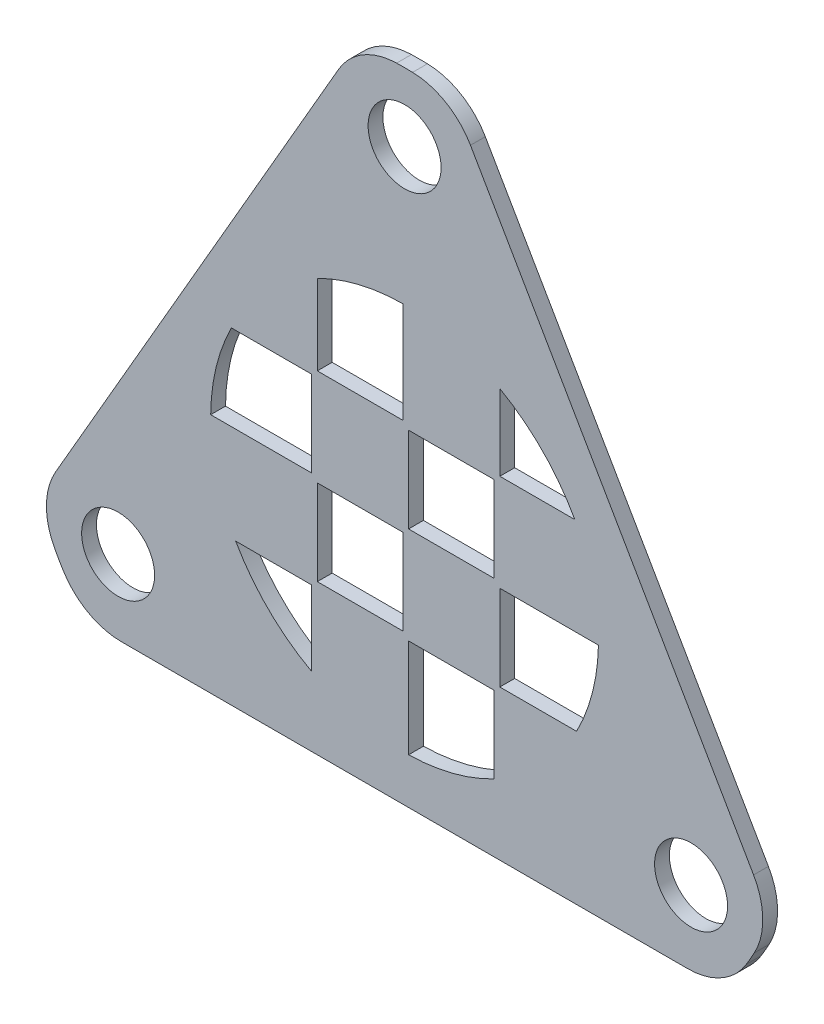
SolidWorks part; units mm, degrees
ref_plane "Спереди" through (0, 0, 0) normal (0, 0, 1) x (1, 0, 0)
ref_plane "Сверху" through (0, 0, 0) normal (0, 1, 0) x (1, 0, 0)
ref_plane "Справа" through (0, 0, 0) normal (1, 0, 0) x (0, 0, -1)
sketch "Sketch1" plane through (0, 0, 0) normal (0, 0, 1) x (1, 0, 0)
  line L0 (3.9, 6.755) -> (7.8, 0) construction
  line L2 (5.85, 10.1325) -> (11.7, 0) construction
  line L4 (7.8, 13.51) -> (15.6, 0) construction
  circle A61 centre (0, 0) radius 20
  circle A131 centre (0, 0) radius 1.25
  circle A484 centre (3.9, 0) radius 1.25
  circle A485 centre (7.8, 0) radius 1.25
  circle A486 centre (11.7, 0) radius 1.25
  circle A487 centre (15.6, 0) radius 1.25
  circle A488 centre (1.95, -3.3775) radius 1.25
  circle A489 centre (3.9, -6.755) radius 1.25
  circle A490 centre (5.85, -10.1325) radius 1.25
  circle A491 centre (7.8, -13.51) radius 1.25
  circle A492 centre (-1.95, -3.3775) radius 1.25
  circle A493 centre (-3.9, -6.755) radius 1.25
  circle A494 centre (-5.85, -10.1325) radius 1.25
  circle A495 centre (-7.8, -13.51) radius 1.25
  circle A496 centre (-3.9, 0) radius 1.25
  circle A497 centre (-7.8, 0) radius 1.25
  circle A498 centre (-11.7, 0) radius 1.25
  circle A499 centre (-15.6, 0) radius 1.25
  circle A500 centre (-1.95, 3.3775) radius 1.25
  circle A501 centre (-3.9, 6.755) radius 1.25
  circle A502 centre (-5.85, 10.1325) radius 1.25
  circle A503 centre (-7.8, 13.51) radius 1.25
  circle A504 centre (1.95, 3.3775) radius 1.25
  circle A505 centre (3.9, 6.755) radius 1.25
  circle A506 centre (5.85, 10.1325) radius 1.25
  circle A507 centre (7.8, 13.51) radius 1.25
  circle A508 centre (5.85, 3.3775) radius 1.25
  circle A509 centre (7.8, 6.755) radius 1.25
  circle A510 centre (9.75, 3.3775) radius 1.25
  circle A511 centre (11.7, 6.755) radius 1.25
  circle A512 centre (9.7491, 10.1341) radius 1.25
  circle A513 centre (13.6509, 3.3759) radius 1.25
  circle A514 centre (5.85, -3.3791) radius 1.25
  circle A515 centre (9.75, -3.3791) radius 1.25
  circle A516 centre (7.8, -6.7566) radius 1.25
  circle A517 centre (11.7, -6.7566) radius 1.25
  circle A518 centre (9.7491, -10.1356) radius 1.25
  circle A519 centre (13.6509, -3.3775) radius 1.25
  circle A520 centre (-0.0013, -6.7573) radius 1.25
  circle A521 centre (1.9487, -10.1348) radius 1.25
  circle A522 centre (-1.9513, -10.1348) radius 1.25
  circle A523 centre (-0.0013, -13.5123) radius 1.25
  circle A524 centre (-3.9032, -13.5123) radius 1.25
  circle A525 centre (3.9005, -13.5123) radius 1.25
  circle A526 centre (-5.8527, -3.3791) radius 1.25
  circle A527 centre (-7.8027, -6.7566) radius 1.25
  circle A528 centre (-9.7527, -3.3791) radius 1.25
  circle A529 centre (-11.7027, -6.7566) radius 1.25
  circle A530 centre (-13.6536, -3.3775) radius 1.25
  circle A531 centre (-9.7518, -10.1356) radius 1.25
  circle A532 centre (-5.8527, 3.3775) radius 1.25
  circle A533 centre (-9.7527, 3.3775) radius 1.25
  circle A534 centre (-7.8027, 6.755) radius 1.25
  circle A535 centre (-11.7027, 6.755) radius 1.25
  circle A536 centre (-9.7518, 10.1341) radius 1.25
  circle A537 centre (-13.6536, 3.3759) radius 1.25
  circle A538 centre (-0.0014, 6.7558) radius 1.25
  circle A539 centre (-1.9514, 10.1333) radius 1.25
  circle A540 centre (1.9486, 10.1333) radius 1.25
  circle A541 centre (-0.0014, 13.5108) radius 1.25
  circle A542 centre (3.9005, 13.5108) radius 1.25
  circle A543 centre (-3.9032, 13.5108) radius 1.25
  circle A544 centre (13.65, -1.1258) radius 2.2517 construction
  circle A545 centre (11.7009, -4.5044) radius 2.2522 construction
  circle A546 centre (9.75, -7.8834) radius 2.2522 construction
  circle A547 centre (7.7987, -11.2591) radius 2.2509 construction
  circle A548 centre (13.65, -1.1258) radius 0.65
  circle A549 centre (11.7009, -4.5044) radius 0.65
  circle A550 centre (9.75, -7.8834) radius 0.65
  circle A551 centre (7.7987, -11.2591) radius 0.65
  circle A552 centre (9.75, -1.1258) radius 0.65
  circle A553 centre (7.8009, -4.5044) radius 0.65
  circle A554 centre (5.85, -7.8834) radius 0.65
  circle A555 centre (3.8987, -11.2591) radius 0.65
  circle A556 centre (5.85, -1.1258) radius 0.65
  circle A557 centre (3.9009, -4.5044) radius 0.65
  circle A558 centre (1.95, -7.8834) radius 0.65
  circle A559 centre (-0.0013, -11.2591) radius 0.65
  circle A560 centre (1.95, -1.1258) radius 0.65
  circle A561 centre (0.0009, -4.5044) radius 0.65
  circle A562 centre (-1.95, -7.8834) radius 0.65
  circle A563 centre (-3.9013, -11.2591) radius 0.65
  circle A564 centre (-1.95, -1.1258) radius 0.65
  circle A565 centre (-3.8991, -4.5044) radius 0.65
  circle A566 centre (-5.85, -7.8834) radius 0.65
  circle A567 centre (-7.8013, -11.2591) radius 0.65
  circle A568 centre (-5.85, -1.1258) radius 0.65
  circle A569 centre (-7.7991, -4.5044) radius 0.65
  circle A570 centre (-9.75, -7.8834) radius 0.65
  circle A572 centre (-9.75, -1.1258) radius 0.65
  circle A573 centre (-11.6991, -4.5044) radius 0.65
  circle A576 centre (-13.65, -1.1258) radius 0.65
  circle A587 centre (0, 2.2517) radius 2.2517 construction
  circle A588 centre (0, 2.2517) radius 0.65
  circle A589 centre (3.9, 2.2517) radius 0.65
  circle A590 centre (7.8, 2.2517) radius 0.65
  circle A591 centre (11.7, 2.2517) radius 0.65
  circle A592 centre (15.6, 2.2517) radius 0.65
  circle A593 centre (1.9491, 5.6297) radius 2.2522 construction
  circle A594 centre (1.9491, 5.6297) radius 0.65
  circle A595 centre (5.8491, 5.6297) radius 0.65
  circle A596 centre (9.7491, 5.6297) radius 0.65
  circle A597 centre (13.6491, 5.6297) radius 0.65
  circle A598 centre (3.8991, 9.0072) radius 2.2522 construction
  circle A599 centre (3.8991, 9.0072) radius 0.65
  circle A600 centre (7.7991, 9.0072) radius 0.65
  circle A601 centre (11.6991, 9.0072) radius 0.65
  circle A602 centre (5.85, 12.3842) radius 2.2517 construction
  circle A603 centre (5.85, 12.3842) radius 0.65
  circle A604 centre (9.75, 12.3842) radius 0.65
  circle A605 centre (5.85, -14.6358) radius 0.65
  circle A606 centre (1.9509, -14.6353) radius 0.65
  circle A607 centre (-1.9491, -14.6353) radius 0.65
  circle A608 centre (-5.85, -14.6358) radius 0.65
  circle A609 centre (-15.6, 2.2517) radius 0.65
  circle A610 centre (-13.65, 5.6281) radius 0.65
  circle A611 centre (-11.7, 9.0056) radius 0.65
  circle A612 centre (-9.75, 12.3842) radius 0.65
  circle A613 centre (-5.85, 12.3842) radius 0.65
  circle A614 centre (-1.95, 12.3842) radius 0.65
  circle A615 centre (1.95, 12.3842) radius 0.65
  circle A616 centre (-7.8, 9.0056) radius 0.65
  circle A617 centre (-9.75, 5.6281) radius 0.65
  circle A618 centre (-11.7, 2.2517) radius 0.65
  circle A619 centre (-3.9, 9.0056) radius 0.65
  circle A620 centre (-5.85, 5.6281) radius 0.65
  circle A621 centre (-7.8, 2.2517) radius 0.65
  circle A622 centre (0, 9.0056) radius 0.65
  circle A623 centre (-1.95, 5.6281) radius 0.65
  circle A624 centre (-3.9, 2.2517) radius 0.65
  circle A625 centre (-15.5991, -4.5044) radius 0.65
  circle A626 centre (-13.65, -7.8834) radius 0.65
  circle A627 centre (-17.55, -7.8834) radius 0.65
  circle A628 centre (-19.5013, -11.2591) radius 0.65
  circle A629 centre (-15.6013, -11.2591) radius 0.65
  circle A630 centre (-11.7013, -11.2591) radius 0.65
  point P51 (0, 0)
  point P125 (-0.0013, -0.0008)
  point P231 (0, 0)
  dimension "D1" = 5
  dimension "D3" = 6
  dimension "D5" = 8
  dimension "D7" = 4
  dimension "D11" = 4
  dimension "D2" = 6
  dimension "D6" = 5
  dimension "D8" = 3
  dimension "D9" = 2
  dimension "D4" = 1.3
  dimension "D10" = 3
ref_plane "Plane1" through (0, 0, 10) normal (0, 0, 1) x (1, 0, 0)
sketch "Sketch2" plane through (0, 0, 10) normal (0, 0, 1) x (1, 0, 0)
  line L0 (-7.65, -15.1815) -> (-7.65, -8.35)
  line L2 (0.35, -16.9964) -> (0.35, -8.35)
  line L4 (-0.15, -16.9993) -> (-0.15, -8.35)
  line L5 (0.1469, -16.9994) -> (0.0704, -8.15) construction
  line L8 (-8.15, -14.919) -> (-8.15, -8.35)
  line L15 (16.9993, 0.15) -> (8.35, 0.15)
  line L17 (16.9964, -0.35) -> (8.35, -0.35)
  line L22 (14.919, 8.15) -> (8.35, 8.15)
  line L24 (15.1815, 7.65) -> (8.35, 7.65)
  line L26 (15.079, -7.85) -> (8.35, -7.85)
  line L28 (14.808, -8.35) -> (8.35, -8.35)
  line L33 (7.85, -15.079) -> (7.85, -8.35)
  line L34 (8.35, -14.808) -> (8.35, -8.35)
  line L36 (7.85, -7.85) -> (7.85, -0.35)
  line L37 (8.35, -7.85) -> (8.35, -0.35)
  line L38 (7.85, -8.35) -> (0.35, -8.35)
  line L39 (7.85, -7.85) -> (0.35, -7.85)
  line L40 (-0.15, -8.35) -> (-7.65, -8.35)
  line L41 (-0.15, -7.85) -> (-7.65, -7.85)
  line L42 (-0.15, -7.85) -> (-0.15, -0.35)
  line L43 (-0.0704, -8.15) -> (-0.1469, -16.9994) construction
  line L44 (0.0678, -7.85) -> (0, 0) construction
  line L45 (0.35, -7.85) -> (0.35, -0.35)
  line L46 (-8.15, -7.85) -> (-15.079, -7.85)
  line L47 (-8.15, -7.85) -> (-8.15, -0.35)
  line L48 (-7.65, -7.85) -> (-7.65, -0.35)
  line L49 (-8.15, -8.35) -> (-14.808, -8.35)
  line L50 (0.003, -0.35) -> (-0.0013, -0.35)
  line L53 (0.0013, 0.15) -> (-0.0013, 0.15)
  line L54 (-0.15, 0.15) -> (-7.65, 0.15)
  line L55 (-0.15, -0.35) -> (-7.65, -0.35)
  line L56 (7.85, -0.35) -> (0.35, -0.35)
  line L59 (7.85, 0.15) -> (0.35, 0.15)
  line L60 (7.85, 0.15) -> (7.85, 7.65)
  line L61 (8.35, 0.15) -> (8.35, 7.65)
  line L62 (-8.15, -0.35) -> (-16.9964, -0.35)
  line L65 (-8.15, 0.15) -> (-16.9993, 0.15)
  line L66 (-8.15, 0.15) -> (-8.15, 7.65)
  line L67 (-7.65, 0.15) -> (-7.65, 7.65)
  line L68 (-0.15, 0.15) -> (-0.15, 7.65)
  line L70 (0, 0) -> (-0.0678, -7.85) construction
  line L71 (0.35, 0.15) -> (0.35, 7.65)
  line L72 (7.85, 8.15) -> (7.85, 15.079)
  line L73 (8.35, 8.15) -> (8.35, 14.808)
  line L74 (7.85, 7.65) -> (0.35, 7.65)
  line L75 (7.85, 8.15) -> (0.35, 8.15)
  line L76 (-0.15, 8.15) -> (-0.15, 16.9993)
  line L79 (0.35, 8.15) -> (0.35, 16.9964)
  line L80 (-0.15, 7.65) -> (-7.65, 7.65)
  line L81 (-0.15, 8.15) -> (-7.65, 8.15)
  line L82 (-8.15, 8.15) -> (-8.15, 14.919)
  line L83 (-7.65, 8.15) -> (-7.65, 15.1815)
  line L84 (-8.15, 7.65) -> (-15.1815, 7.65)
  line L85 (-8.15, 8.15) -> (-14.919, 8.15)
  circle A52 centre (0, 0) radius 17
  circle A53 centre (0, 0) radius 18
  dimension "D1" = 36
  dimension "D4" = 2
  dimension "D2" = 2
  dimension "D5" = 2
  dimension "D6" = 8
  dimension "D7" = 0.5
  dimension "D8" = 8
  dimension "D9" = 8
  dimension "D3" = 8
  dimension "D10" = 0.5
  dimension "D11" = 0.5
extrude "Boss-Extrude1" add sketch "Sketch2" against normal blind 1.3
sketch "Sketch18" plane through (0, 0, 8.7) normal (0, 0, 1) x (1, 0, 0)
  line L0 (-7.85, -15.079) -> (-7.85, -8.15)
  line L2 (0.15, -16.9993) -> (0.15, -8.15)
  line L4 (-0.15, -16.9993) -> (-0.15, -8.15)
  line L5 (0.1469, -16.9994) -> (0.0704, -8.15) construction
  line L8 (-8.15, -14.919) -> (-8.15, -8.15)
  line L15 (16.9993, 0.15) -> (8.15, 0.15)
  line L17 (16.9993, -0.15) -> (8.15, -0.15)
  line L22 (14.919, 8.15) -> (8.15, 8.15)
  line L24 (15.079, 7.85) -> (8.15, 7.85)
  line L26 (15.079, -7.85) -> (8.15, -7.85)
  line L28 (14.919, -8.15) -> (8.15, -8.15)
  line L33 (7.85, -15.079) -> (7.85, -8.15)
  line L34 (8.15, -14.919) -> (8.15, -8.15)
  line L36 (7.85, -7.85) -> (7.85, -0.15)
  line L37 (8.15, -7.85) -> (8.15, -0.15)
  line L38 (7.85, -8.15) -> (0.15, -8.15)
  line L39 (7.85, -7.85) -> (0.15, -7.85)
  line L40 (-0.15, -8.15) -> (-7.85, -8.15)
  line L41 (-0.15, -7.85) -> (-7.85, -7.85)
  line L42 (-0.15, -7.85) -> (-0.15, -0.15)
  line L43 (-0.0704, -8.15) -> (-0.1469, -16.9994) construction
  line L44 (0.0678, -7.85) -> (0, 0) construction
  line L45 (0.15, -7.85) -> (0.15, -0.15)
  line L46 (-8.15, -7.85) -> (-15.079, -7.85)
  line L47 (-8.15, -7.85) -> (-8.15, -0.15)
  line L48 (-7.85, -7.85) -> (-7.85, -0.15)
  line L49 (-8.15, -8.15) -> (-14.919, -8.15)
  line L50 (0.0013, -0.15) -> (-0.0013, -0.15)
  line L53 (0.0013, 0.15) -> (-0.0013, 0.15)
  line L54 (-0.15, 0.15) -> (-7.85, 0.15)
  line L55 (-0.15, -0.15) -> (-7.85, -0.15)
  line L56 (7.85, -0.15) -> (0.15, -0.15)
  line L59 (7.85, 0.15) -> (0.15, 0.15)
  line L60 (7.85, 0.15) -> (7.85, 7.85)
  line L61 (8.15, 0.15) -> (8.15, 7.85)
  line L62 (-8.15, -0.15) -> (-16.9993, -0.15)
  line L65 (-8.15, 0.15) -> (-16.9993, 0.15)
  line L66 (-8.15, 0.15) -> (-8.15, 7.85)
  line L67 (-7.85, 0.15) -> (-7.85, 7.85)
  line L68 (-0.15, 0.15) -> (-0.15, 7.85)
  line L70 (0, 0) -> (-0.0678, -7.85) construction
  line L71 (0.15, 0.15) -> (0.15, 7.85)
  line L72 (7.85, 8.15) -> (7.85, 15.079)
  line L73 (8.15, 8.15) -> (8.15, 14.919)
  line L74 (7.85, 7.85) -> (0.15, 7.85)
  line L75 (7.85, 8.15) -> (0.15, 8.15)
  line L76 (-0.15, 8.15) -> (-0.15, 16.9993)
  line L79 (0.15, 8.15) -> (0.15, 16.9993)
  line L80 (-0.15, 7.85) -> (-7.85, 7.85)
  line L81 (-0.15, 8.15) -> (-7.85, 8.15)
  line L82 (-8.15, 8.15) -> (-8.15, 14.919)
  line L83 (-7.85, 8.15) -> (-7.85, 15.079)
  line L84 (-8.15, 7.85) -> (-15.079, 7.85)
  line L85 (-8.15, 8.15) -> (-14.919, 8.15)
  circle A52 centre (0, 0) radius 17
  circle A53 centre (0, 0) radius 18
  dimension "D1" = 36
  dimension "D4" = 2
  dimension "D2" = 2
  dimension "D5" = 2
  dimension "D6" = 8
  dimension "D8" = 8
  dimension "D9" = 8
  dimension "D3" = 8
extrude "Boss-Extrude10" add sketch "Sketch18" along normal blind 1.3 contours A52 L72 L75 L79 | A52 L15 L61 L24 | L80 L68 L54 L67 | L56 L36 L39 L45 | A52 L34 L28 | A52 L0 L40 L4 | A52 L62 L47 L46 | A52 L82 L85
sketch "Sketch3" plane through (0, 0, 8.7) normal (0, 0, -1) x (-1, 0, 0)
  circle A0 centre (0, 0) radius 17.6
  circle A1 centre (0, 0) radius 35
  circle M33 centre (0, 0) radius 18
extrude "Boss-Extrude2" add sketch "Sketch3" against normal blind 1.3 contours A1 M33
sketch "Sketch4" plane through (0, 0, 8.7) normal (0, 0, -1) x (-1, 0, 0)
  circle A0 centre (0, 0) radius 29 construction
  circle A1 centre (0, 29) radius 3.2
  circle A2 centre (25.1147, -14.5) radius 3.2
  circle A3 centre (-25.1147, -14.5) radius 3.2
  point P11 (0, 0)
  dimension "D1" = 3
sketch "Sketch7" plane through (0, 0, 8.7) normal (0, 0, -1) x (-1, 0, 0)
  line L1 (0, 42) -> (-36.3731, -21)
  line L2 (-36.3731, -21) -> (36.3731, -21)
  line L3 (36.3731, -21) -> (0, 42)
  circle A2 centre (0, 0) radius 21 construction
  circle A3 centre (0, 0) radius 59.1314
extrude "Cut-Extrude1" cut sketch "Sketch7" against normal through all both and the other way through all
fillet "Fillet1" radius 6 6 edges at (-32.1865, -13.7487, 9.35) (-4.1865, 34.7487, 9.35) (28, -21, 9.35) (-28, -21, 9.35) (4.1865, 34.7487, 9.35) (32.1865, -13.7487, 9.35)
extrude "Cut-Extrude2" cut sketch "Sketch4" against normal blind 10
